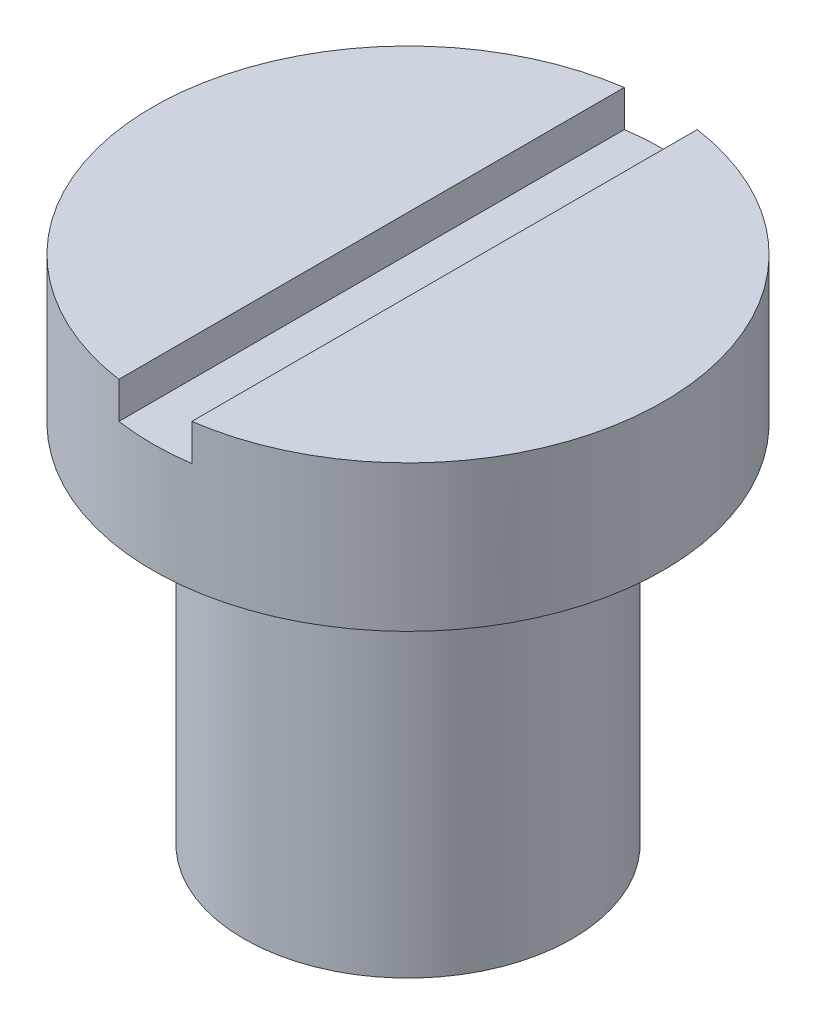
SolidWorks part; units mm, degrees
ref_plane "前视基准面" through (0, 0, 0) normal (0, 0, 1) x (1, 0, 0)
ref_plane "上视基准面" through (0, 0, 0) normal (0, 1, 0) x (1, 0, 0)
ref_plane "右视基准面" through (0, 0, 0) normal (1, 0, 0) x (0, 0, -1)
sketch "草图2" plane through (0, 0, 0) normal (0, 0, 1) x (1, 0, 0)
  line L0 (0, 0) -> (0, 14)
  line L1 (0, 14) -> (7, 14)
  line L2 (7, 14) -> (7, 10)
  line L3 (7, 10) -> (4.5, 10)
  line L4 (4.5, 10) -> (4.5, 0)
  line L5 (4.5, 0) -> (0, 0)
  dimension "D2" = 7
  dimension "D3" = 4.5
  dimension "D4" = 4
  dimension "D5" = 10
revolve "旋转1" add sketch "草图2" angle 360 about L0
sketch "草图3" plane through (0, 0, 0) normal (0, 0, 1) x (1, 0, 0)
  line L0 (7, 14) -> (-7, 14) construction
  line L1 (-1, 13) -> (1, 13)
  line L2 (-1, 13) -> (-1, 15)
  line L3 (-1, 15) -> (1, 15)
  line L4 (1, 13) -> (1, 15)
  line L5 (-1, 13) -> (1, 15) construction
  line L6 (-1, 15) -> (1, 13) construction
  point P0 (0, 14)
  dimension "D1" = 2
  dimension "D2" = 2
extrude "切除-拉伸1" cut sketch "草图3" against normal mid plane 20
